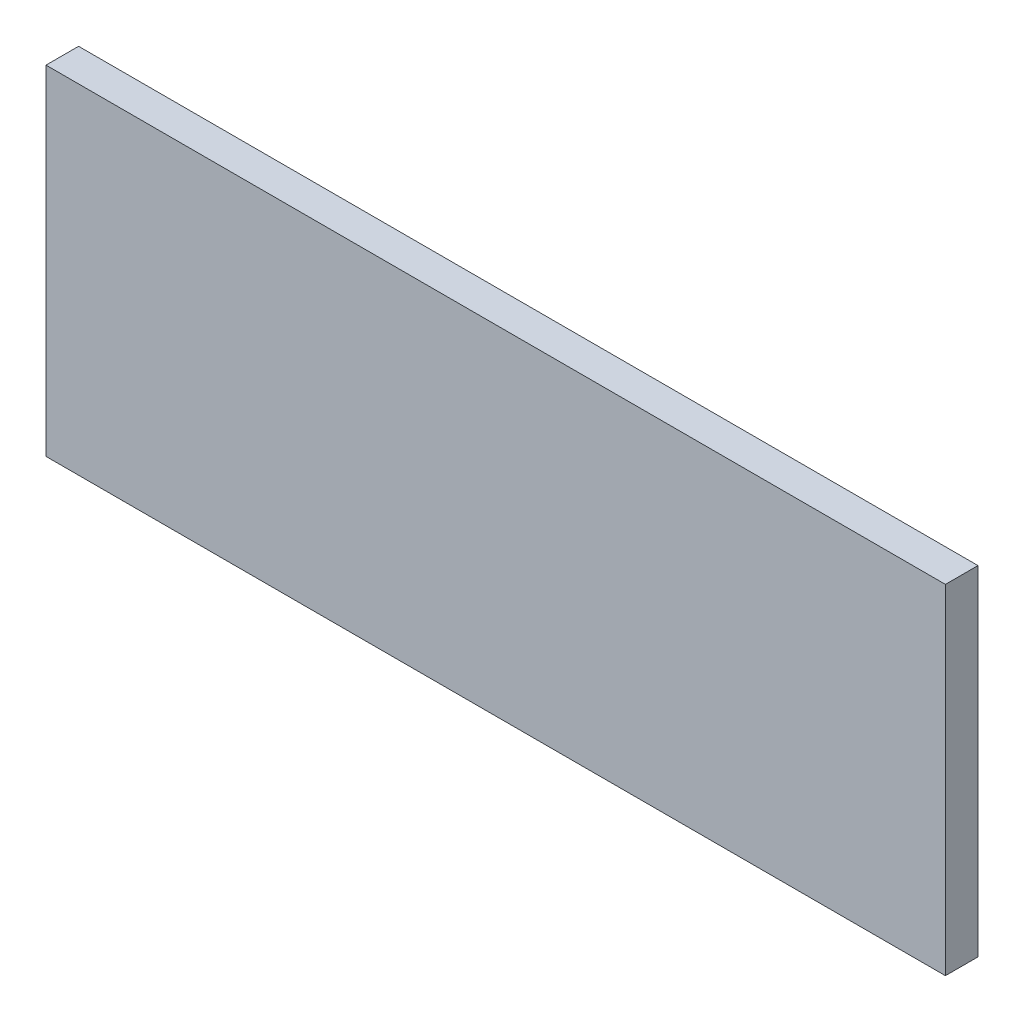
SolidWorks part; units mm, degrees
material "Гофрированная бумага"
ref_plane "Спереди" through (0, 0, 0) normal (0, 0, 1) x (1, 0, 0)
ref_plane "Сверху" through (0, 0, 0) normal (0, 1, 0) x (1, 0, 0)
ref_plane "Справа" through (0, 0, 0) normal (1, 0, 0) x (0, 0, -1)
sketch "Эскиз1" plane through (0, 0, 0) normal (0, 0, 1) x (1, 0, 0)
  line L1 (-138, -52) -> (138, -52)
  line L2 (-138, -52) -> (-138, 52)
  line L3 (-138, 52) -> (138, 52)
  line L4 (138, -52) -> (138, 52)
  line L5 (-138, -52) -> (138, 52) construction
  line L6 (-138, 52) -> (138, -52) construction
  point P0 (0, 0)
  dimension "D1" = 276
  dimension "D2" = 104
extrude "Бобышка-Вытянуть1" add sketch "Эскиз1" along normal mid plane 10
